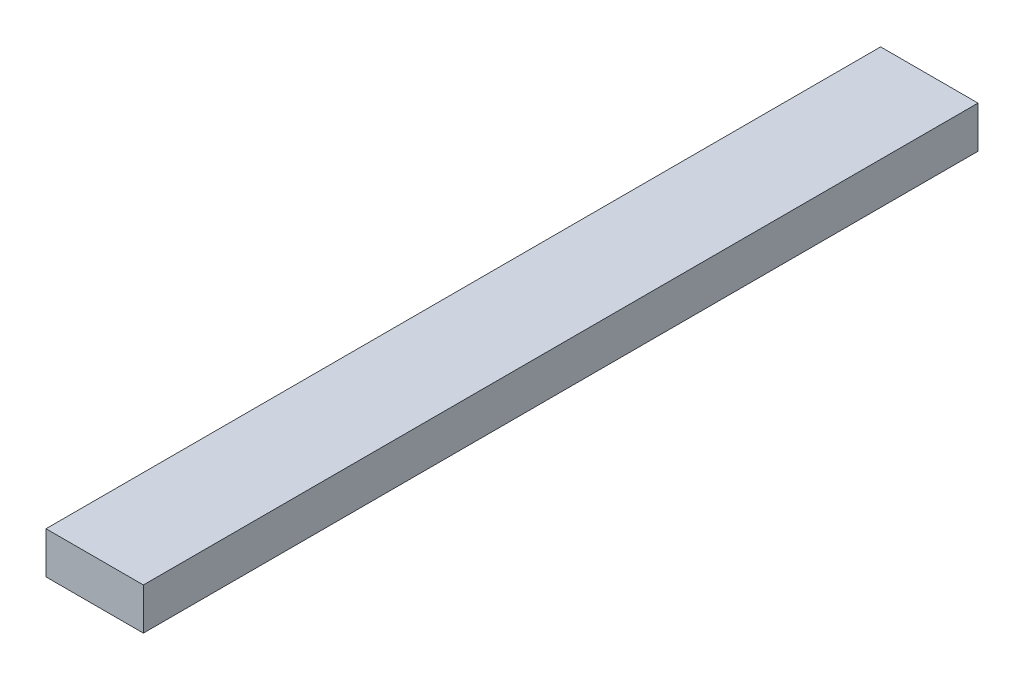
SolidWorks part; units mm, degrees
ref_plane "Front Plane" through (0, 0, 0) normal (0, 0, 1) x (1, 0, 0)
ref_plane "Top Plane" through (0, 0, 0) normal (0, 1, 0) x (1, 0, 0)
ref_plane "Right Plane" through (0, 0, 0) normal (1, 0, 0) x (0, 0, -1)
sketch "Sketch1" plane through (0, 0, 0) normal (0, 0, 1) x (1, 0, 0)
  line L1 (44.45, 19.05) -> (-44.45, 19.05)
  line L2 (44.45, 19.05) -> (44.45, -19.05)
  line L3 (44.45, -19.05) -> (-44.45, -19.05)
  line L4 (-44.45, 19.05) -> (-44.45, -19.05)
  line L5 (44.45, 19.05) -> (-44.45, -19.05) construction
  line L6 (44.45, -19.05) -> (-44.45, 19.05) construction
  point P0 (0, 0)
  dimension "D1" = 88.9
  dimension "D2" = 38.1
extrude "Boss-Extrude1" add sketch "Sketch1" along normal mid plane 762
